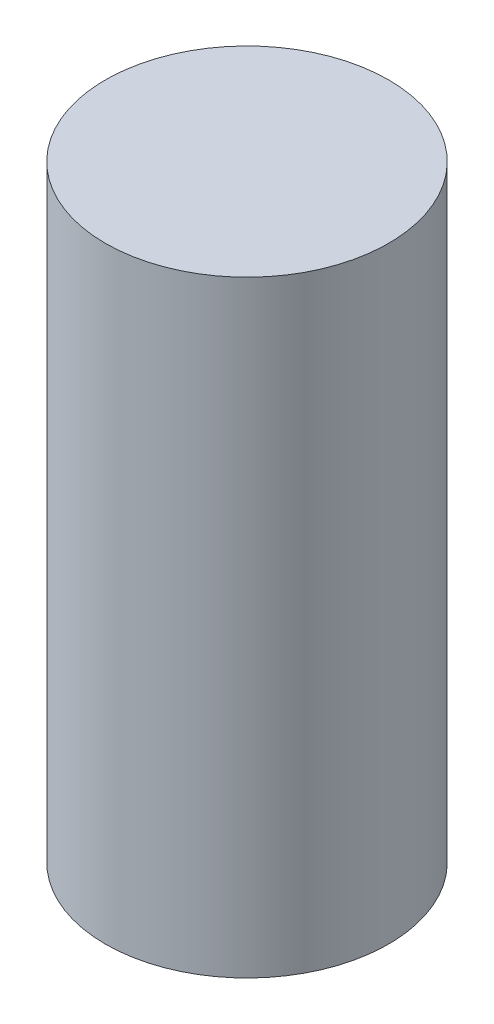
SolidWorks part; units mm, degrees
ref_plane "Front Plane" through (0, 0, 0) normal (0, 0, 1) x (1, 0, 0)
ref_plane "Top Plane" through (0, 0, 0) normal (0, 1, 0) x (1, 0, 0)
ref_plane "Right Plane" through (0, 0, 0) normal (1, 0, 0) x (0, 0, -1)
sketch "Sketch1" plane through (0, 0, 0) normal (0, 1, 0) x (1, 0, 0)
  circle A0 centre (0, 0) radius 0.875
  dimension "D1" = 1.75
extrude "Boss-Extrude1" add sketch "Sketch1" along normal blind 3.75
